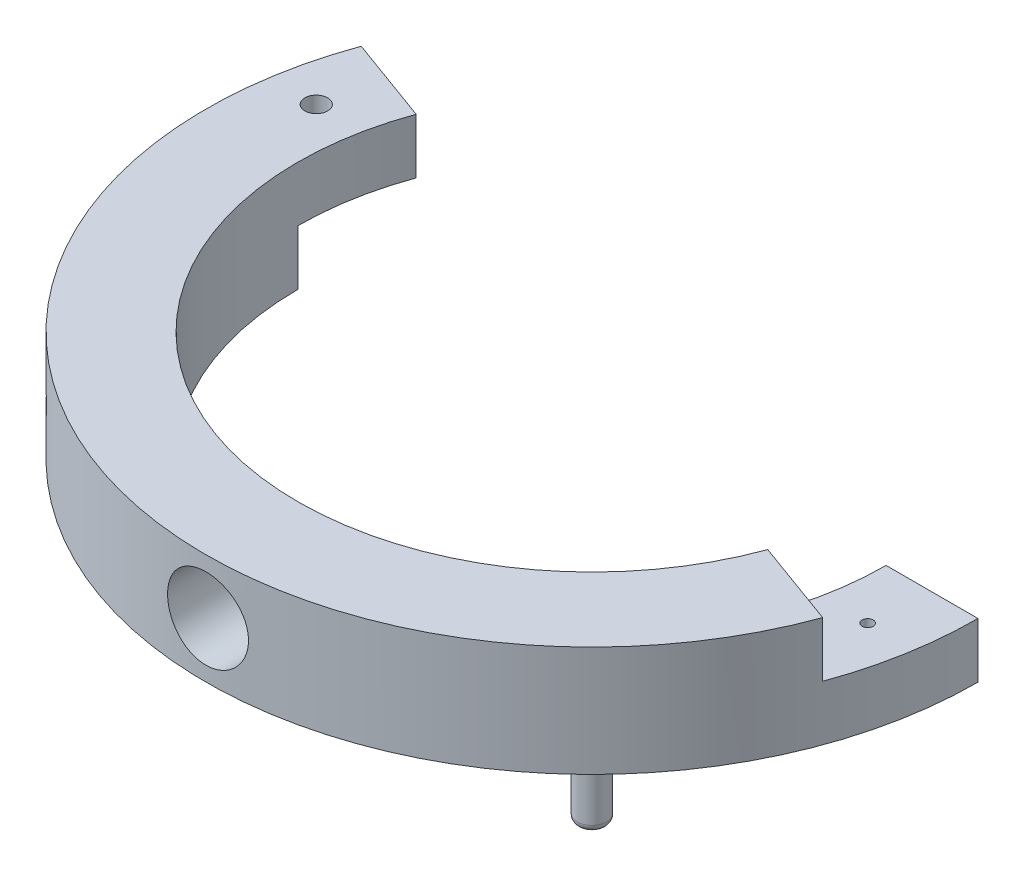
SolidWorks part; units mm, degrees
ref_plane "Front Plane" through (0, 0, 0) normal (0, 0, 1) x (1, 0, 0)
ref_plane "Top Plane" through (0, 0, 0) normal (0, 1, 0) x (1, 0, 0)
ref_plane "Right Plane" through (0, 0, 0) normal (1, 0, 0) x (0, 0, -1)
sketch "Sketch2" plane through (0, 0, 0) normal (0, 1, 0) x (1, 0, 0)
  line L0 (-105, 0) -> (-80, 0)
  line L1 (80, 0) -> (105, 0)
  arc A0 (80, 0) -> (-80, 0) centre (0, 0) cw
  arc A1 (105, 0) -> (-105, 0) centre (0, 0) cw
extrude "Boss-Extrude1" add sketch "Sketch2" along normal blind 30
sketch "Sketch3" plane through (0, 30, 0) normal (0, 1, 0) x (1, 0, 0)
  line L0 (-98.6677, 35.9121) -> (-75.1754, 27.3616)
  line L1 (-80, 0) -> (-105, 0)
  arc A0 (-80, 0) -> (-75.1754, 27.3616) centre (0, 0) cw
  arc A1 (-105, 0) -> (-98.6677, 35.9121) centre (0, 0) cw
extrude "Boss-Extrude2" add sketch "Sketch3" against normal blind 15 contours A1 L0 A0 L1
sketch "Sketch4" plane through (0, 30, 0) normal (0, 1, 0) x (1, 0, 0)
  line L0 (105, 0) -> (80, 0) construction
  line L1 (80, 0) -> (105, 0)
  line L2 (75.1754, -27.3616) -> (98.6677, -35.9121)
  arc A0 (80, 0) -> (75.1754, -27.3616) centre (0, 0) cw
  arc A1 (-75.1754, 27.3616) -> (80, 0) centre (0, 0) ccw construction
  arc A2 (105, 0) -> (98.6677, -35.9121) centre (0, 0) cw
  arc A3 (-98.6677, 35.9121) -> (105, 0) centre (0, 0) ccw construction
extrude "Cut-Extrude1" cut sketch "Sketch4" against normal blind 15 contours A2 L2 A0 L1
sketch "Sketch5" plane through (0, 15, 0) normal (0, 1, 0) x (1, 0, 0)
  line L2 (80, 0) -> (105, 0) construction
  line L3 (75.1754, -27.3616) -> (98.6677, -35.9121) construction
  circle A0 centre (91.0881, -16.1) radius 1.5
  dimension "D1" = 3
  dimension "D2" = 92.5
  dimension "D3" = 16.1
  dimension "D4" = 16.0249
extrude "Cut-Extrude2" cut sketch "Sketch5" against normal blind 15 contours A0
sketch "Sketch6" plane through (0, 0, 0) normal (0, -1, 0) x (-1, 0, 0)
  line L0 (-91.0881, -17.6) -> (-91.0881, -14.6) construction
  line L1 (-89.5881, -16.1) -> (-92.5881, -16.1) construction
  circle A0 centre (-91.0881, -16.1) radius 1.5 construction
  circle A1 centre (-91.0881, -16.1) radius 3.1
  dimension "D1" = 6.2
extrude "Cut-Extrude3" cut sketch "Sketch6" against normal blind 5
sketch "Sketch7" plane through (0, 15, 0) normal (0, -1, 0) x (1, 0, 0)
  line L0 (-80, 0) -> (-105, 0) construction
  line L1 (-98.6677, -35.9121) -> (-75.1754, -27.3616) construction
  circle A0 centre (-91.0881, -16.1) radius 1.5
  dimension "D2" = 3
  dimension "D3" = 16.1
  dimension "D1" = 92.5
  dimension "D4" = 16.0249
extrude "Cut-Extrude4" cut sketch "Sketch7" against normal blind 15
sketch "Sketch8" plane through (0, 30, 0) normal (0, 1, 0) x (1, 0, 0)
  line L0 (-92.5881, 16.1) -> (-89.5881, 16.1) construction
  circle A0 centre (-91.0881, 16.1) radius 1.5 construction
  circle A1 centre (-91.0881, 16.1) radius 3.1
extrude "Cut-Extrude5" cut sketch "Sketch8" against normal blind 5
ref_plane "Plane1" through (0, 0, 105) normal (0, 0, 1) x (1, 0, 0)
sketch "Sketch11" plane through (0, 0, 105) normal (0, 0, 1) x (1, 0, 0)
  line L0 (0, 0) -> (0, 30) construction
  line L1 (98.6677, 30) -> (-105, 30) construction
  circle A0 centre (0, 15) radius 7.5
  dimension "D1" = 15
extrude "Cut-Extrude6" cut sketch "Sketch11" against normal blind 30
sketch "Sketch12" plane through (0, 0, 105) normal (0, 0, 1) x (1, 0, 0)
  line L0 (0, 22.5) -> (0, 7.5) construction
  circle A0 centre (0, 15) radius 7.5 construction
  circle A1 centre (0, 15) radius 11
  dimension "D1" = 22
extrude "Cut-Extrude7" cut sketch "Sketch12" against normal blind 20
sketch "Sketch13" plane through (0, 0, 0) normal (0, -1, 0) x (1, 0, 0)
  line L0 (0, 0) -> (0, 105) construction
  line L1 (0, 0) -> (-74.2462, 74.2462) construction
  arc A0 (105, 0) -> (-105, 0) centre (0, 0) ccw construction
  circle A1 centre (-65.4074, 65.4074) radius 4
  dimension "D2" = 92.5
  dimension "D1" = 45
extrude "Boss-Extrude3" add sketch "Sketch13" along normal blind 20
fillet "Fillet1" radius 2 1 edges at (-65.4074, -20, 61.4074)
mirror "Mirror1" about plane through (0, 0, 0) normal (1, 0, 0) of "Boss-Extrude3", "Fillet1"
ref_plane "Plane2" through (-74.2462, 0, 74.2462) normal (-0.7071, 0, 0.7071) x (0, -1, 0)
sketch "Sketch14" plane through (-74.2462, 0, 74.2462) normal (-0.7071, 0, 0.7071) x (0, -1, 0)
  line L0 (0, 0) -> (-30, 0) construction
  line L1 (-30, 105) -> (-30, -95.1623) construction
  circle A0 centre (-15, 0) radius 4
extrude "Cut-Extrude8" cut sketch "Sketch14" against normal blind 40
